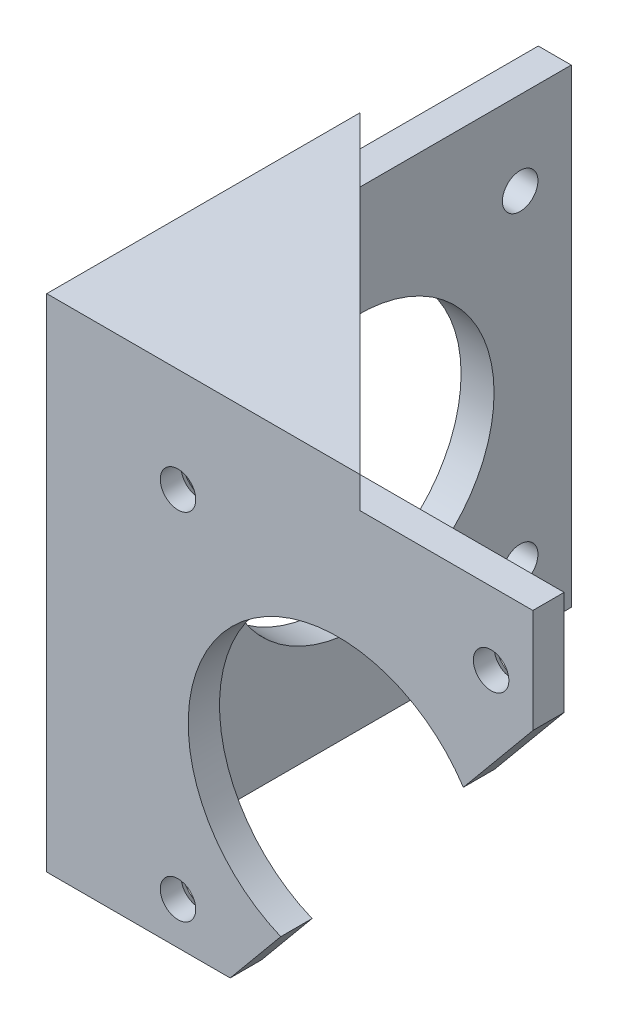
SolidWorks part; units mm, degrees
ref_plane "Спереди" through (0, 0, 0) normal (0, 0, 1) x (1, 0, 0)
ref_plane "Сверху" through (0, 0, 0) normal (0, 1, 0) x (1, 0, 0)
ref_plane "Справа" through (0, 0, 0) normal (1, 0, 0) x (0, 0, -1)
sketch "Эскиз1" plane through (0, 0, 0) normal (0, 0, 1) x (1, 0, 0)
  line L3 (34, 34) -> (34, 37.9632)
  line L4 (34, 37.9632) -> (-6, 37.9632)
  line L6 (-6, -4.0368) -> (5, -4.0368)
  line L8 (34, 34) -> (34, 31)
  line L9 (34, 31) -> (5, -4.0368)
  line L11 (-1.7, 37.9632) -> (-12.576, 37.9632)
  line L12 (-12.576, 37.9632) -> (-12.576, -4.0368)
  line L13 (-12.576, -4.0368) -> (-6, -4.0368)
  circle A0 centre (30, 34) radius 1.7
  circle A1 centre (0, 34) radius 1.7
  circle A2 centre (0, 0) radius 1.7
extrude "Бобышка-Вытянуть1" add sketch "Эскиз1" along normal blind 3 contours L12 L13 L6 L9 L8 L3 L4 L11 A2 A1 A0
sketch "Эскиз2" plane through (0, 0, 0) normal (0, 0, -1) x (-1, 0, 0)
  line L0 (12.576, 37.9632) -> (9.4149, 37.9632)
  line L1 (-34, 37.9632) -> (12.576, 37.9632) construction
  line L2 (9.4149, 37.9632) -> (9.4149, -4.0368)
  line L3 (12.576, -4.0368) -> (-5, -4.0368) construction
  line L4 (9.4149, -4.0368) -> (12.576, -4.0368)
  line L5 (12.576, 37.9632) -> (12.576, -4.0368) construction
  line L6 (12.576, -4.0368) -> (12.576, 37.9632)
extrude "Бобышка-Вытянуть2" add sketch "Эскиз2" along normal blind 45
sketch "Эскиз3" plane through (-9.4149, 0, 0) normal (1, 0, 0) x (0, 0, -1)
  line L0 (0, 37.9632) -> (0, 32.9632)
  line L1 (0, 37.9632) -> (0, 31) construction
  line L2 (0, 32.9632) -> (8.2, 32.9632)
  line L3 (8.2, 32.9632) -> (39.2, 32.9632)
  line L4 (39.2, 32.9632) -> (39.2, 1.9632)
  line L5 (39.2, 1.9632) -> (8.2, 1.9632)
  line L6 (8.2, 32.9632) -> (23.7, 32.9632)
  line L7 (23.7, 32.9632) -> (23.7, 17.4632)
  circle A0 centre (39.2, 32.9632) radius 1.7
  circle A1 centre (8.2, 32.9632) radius 1.7
  circle A2 centre (39.2, 1.9632) radius 1.7
  circle A3 centre (8.2, 1.9632) radius 1.7
  circle A4 centre (23.7, 17.4632) radius 13
extrude "Вырез-Вытянуть1" cut sketch "Эскиз3" against normal blind 45
sketch "Эскиз4" plane through (0, 0, 0) normal (0, 0, -1) x (-1, 0, 0)
  circle A0 centre (-15.3362, 15.0854) radius 14.3572
extrude "Вырез-Вытянуть2" cut sketch "Эскиз4" against normal blind 5
sketch "Эскиз5" plane through (-9.4149, 0, 0) normal (1, 0, 0) x (0, 0, -1)
  line L0 (45, 37.9632) -> (0, 37.9632) construction
  line L1 (44.0943, 37.9632) -> (47.8505, 37.9632)
  line L2 (44.0943, 37.9632) -> (44.0943, -4.9263)
  line L3 (44.0943, -4.9263) -> (47.8505, -4.9263)
  line L4 (47.8505, 37.9632) -> (47.8505, -4.9263)
extrude "Вырез-Вытянуть3" cut sketch "Эскиз5" against normal blind 5
chamfer "Фаска1" distance 1 angle 45 3 edges at (1.7, 0, 0) (1.7, 34, 0) (31.7, 34, 0)
sketch "Эскиз6" plane through (0, 37.9632, 0) normal (0, 1, 0) x (1, 0, 0)
  line L0 (34, -3) -> (34, 0)
  line L1 (34, 0) -> (-9.4149, 0)
  line L2 (-9.4149, 0) -> (-9.4149, 44.0943)
  line L3 (-9.4149, 44.0943) -> (-12.576, 44.0943)
  line L4 (-12.576, 44.0943) -> (-12.576, -3)
  line L5 (-12.576, -3) -> (34, -3)
extrude "Бобышка-Вытянуть3" add sketch "Эскиз6" along normal blind 3
sketch "Эскиз7" plane through (0, 40.9632, 0) normal (0, 1, 0) x (1, 0, 0)
  line L0 (17.424, -3) -> (-12.576, -3)
  line L1 (-12.576, -3) -> (34, -3) construction
  line L2 (-12.576, -3) -> (-12.576, 27)
  line L3 (-12.576, 44.0943) -> (-12.576, -3) construction
  line L4 (17.424, -3) -> (-12.576, 27)
extrude "Бобышка-Вытянуть4" add sketch "Эскиз7" along normal blind 3
